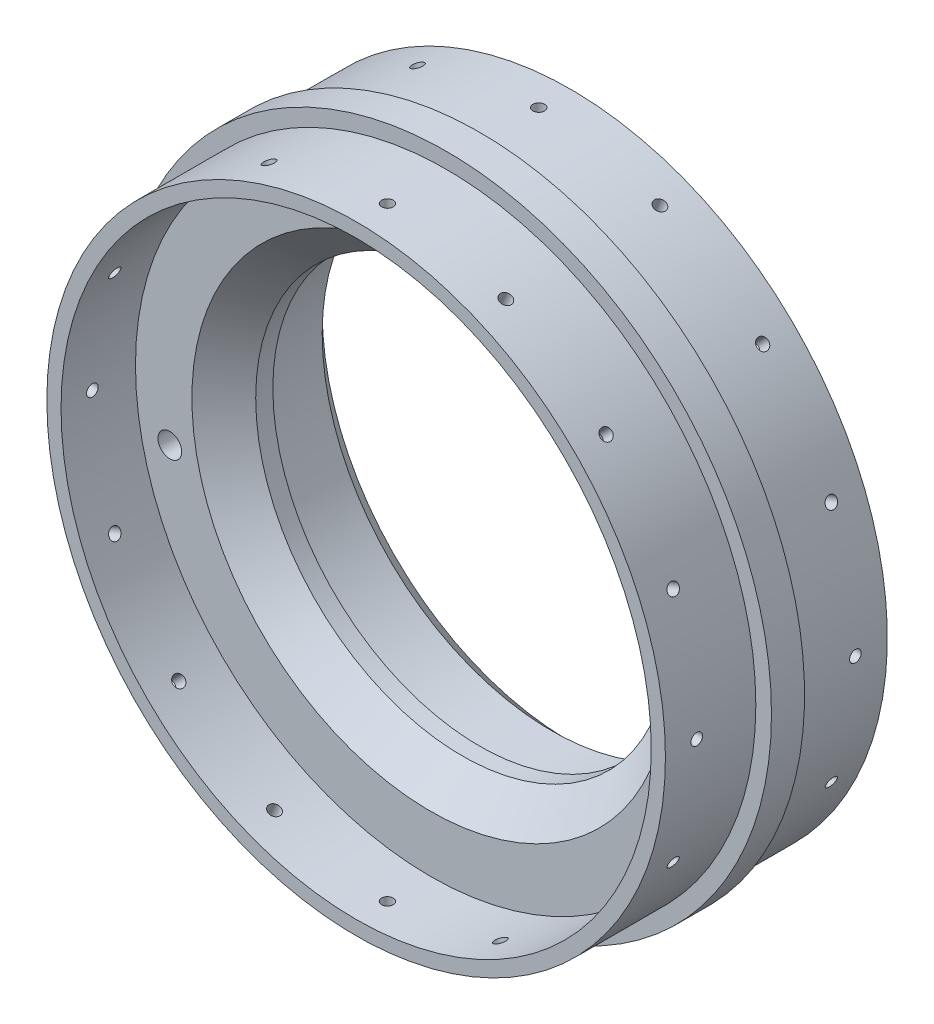
SolidWorks part; units mm, degrees
ref_plane "Front Plane" through (0, 0, 0) normal (0, 0, 1) x (1, 0, 0)
ref_plane "Top Plane" through (0, 0, 0) normal (0, 1, 0) x (1, 0, 0)
ref_plane "Right Plane" through (0, 0, 0) normal (1, 0, 0) x (0, 0, -1)
sketch "Sketch5" plane through (0, 0, 0) normal (0, 0, 1) x (1, 0, 0)
  circle A0 centre (0, 0) radius 69.85
extrude "Extrude1" add sketch "Sketch5" along normal blind 46.101
sketch "Sketch8" plane through (0, 0, 46.101) normal (0, 0, 1) x (1, 0, 0)
  circle A0 centre (0, 0) radius 44.45
extrude "Extrude4" cut sketch "Sketch8" against normal through all
sketch "Sketch6" plane through (0, 0, 46.101) normal (0, 0, 1) x (1, 0, 0)
  circle A0 centre (0, 0) radius 66.4845
extrude "Extrude2" cut sketch "Sketch6" against normal blind 19.431 flip side to cut
sketch "Sketch7" plane through (0, 0, 46.101) normal (0, 0, 1) x (1, 0, 0)
  circle A0 centre (0, 0) radius 63.4365
extrude "Extrude3" cut sketch "Sketch7" against normal blind 16.002
chamfer "Chamfer1" distance 6.858 distance2 6.858 1 edges at (44.45, 0, 30.099)
sketch "Sketch9" plane through (0, 0, 0) normal (0, 0, -1) x (-1, 0, 0)
  circle A0 centre (0, 0) radius 68.0847
extrude "Extrude5" cut sketch "Sketch9" against normal blind 19.558 flip side to cut
sketch "Sketch10" plane through (0, 0, 0) normal (0, 0, -1) x (-1, 0, 0)
  circle A0 centre (0, 0) radius 65.0367
  circle A1 centre (0, 0) radius 53.7845
extrude "Extrude6" cut sketch "Sketch10" against normal blind 9.525
sketch "Sketch11" plane through (0, 0, 0) normal (0, 0, -1) x (-1, 0, 0)
  circle A0 centre (0, 0) radius 49.3395
  dimension "D1" = 98.679
extrude "Extrude7" cut sketch "Sketch11" against normal blind 19.558
chamfer "Chamfer2" distance 4.064 angle 45 1 edges at (-49.3395, 0, 0)
ref_plane "Plane1" through (0, 0, 39.37) normal (0, 0, 1) x (1, 0, 0)
ref_plane "Plane2" through (0, 0, 6.858) normal (0, 0, -1) x (-1, 0, 0)
sketch "Sketch13" plane through (0, 0, 6.858) normal (0, 0, -1) x (-1, 0, 0)
  line L0 (0, 0) -> (0, 68.0847) construction
  circle A0 centre (0, 0) radius 68.0847 construction
ref_plane "Plane3" through (0, 68.0847, 6.858) normal (0, 1, 0) x (-1, 0, 0)
sketch "Sketch15" plane through (0, 0, 39.37) normal (0, 0, 1) x (1, 0, 0)
  line L0 (0, 0) -> (0, 66.4845) construction
  line L1 (0, 0) -> (0, 68.0847) construction
  circle A0 centre (0, 0) radius 66.4845 construction
ref_plane "Plane4" through (0, 66.4845, 39.37) normal (0, 1, 0) x (-1, 0, 0)
hole_wizard "M3x0.5 Tapped Hole2" positions "Sketch20" profile "Sketch19" tap size "M3x0.5" standard "Ansi Metric"
sketch "Sketch20" plane through (0, 68.0847, 6.858) normal (0, 1, 0) x (-1, 0, 0)
  point P1 (0, 0)
sketch "Sketch19" plane through (0, 68.0847, 6.858) normal (1, 0, 0) x (0, 0, 1)
  line L0 (0, 0) -> (0, 9.3871)
  line L1 (0, 9.3871) -> (1.25, 8.636)
  line L2 (1.25, 8.636) -> (1.25, 0)
  line L5 (1.25, 0) -> (0, 0)
  line L10 (0, 9.3871) -> (-1.25, 8.636) construction
  line L11 (0, -6.35) -> (0, 107.95) construction
  dimension "Tap Drill Dia." = 2.5
  dimension "Tap Drill Depth" = 8.636
  dimension "Drill Angle" = 118
cosmetic thread "Hole Thread2" parameters "D1"=3.06, "D2"=3
hole_wizard "M3x0.5 Tapped Hole1" positions "Sketch26" profile "Sketch25" tap size "M3x0.5" standard "Ansi Metric"
sketch "Sketch26" plane through (0, 66.4845, 39.37) normal (0, 1, 0) x (-1, 0, 0)
  point P1 (0, 0)
sketch "Sketch25" plane through (0, 66.4845, 39.37) normal (1, 0, 0) x (0, 0, 1)
  line L0 (0, 0) -> (0, 9.3871)
  line L1 (0, 9.3871) -> (1.25, 8.636)
  line L2 (1.25, 8.636) -> (1.25, 0)
  line L5 (1.25, 0) -> (0, 0)
  line L10 (0, 9.3871) -> (-1.25, 8.636) construction
  line L11 (0, -6.35) -> (0, 107.95) construction
  dimension "Tap Drill Dia." = 2.5
  dimension "Tap Drill Depth" = 8.636
  dimension "Drill Angle" = 118
cosmetic thread "Hole Thread1" parameters "D1"=3.0603, "D2"=3
pattern_circular "CirPattern1" count 16 over 360 about axis through (0, 0, 19.558) along (0, 0, -1) of "M3x0.5 Tapped Hole2", "M3x0.5 Tapped Hole1"
ref_plane "Plane5" through (0, 0, 23.114) normal (0, 0, 1) x (1, 0, 0)
sketch "Sketch27" plane through (0, 0, 23.114) normal (0, 0, 1) x (1, 0, 0)
  line L0 (0, -65.0367) -> (0, -68.0847) construction
  arc A0 (0, -69.85) -> (13.6271, -68.5079) centre (0, 0) ccw construction
  circle A1 centre (0, 0) radius 69.85 construction
ref_plane "Plane6" through (13.6271, -68.5079, 23.114) normal (0.1951, -0.9808, 0) x (0.9808, 0.1951, 0)
hole_wizard "#21 (0.159) Diameter Hole1" positions "Sketch29" profile "Sketch28" hole size "#21" standard "Ansi Inch"
sketch "Sketch29" plane through (13.6271, -68.5079, 23.114) normal (0.1951, -0.9808, 0) x (0.9808, 0.1951, 0)
  point P1 (0, 0)
sketch "Sketch28" plane through (13.6271, -68.5079, 23.114) normal (0, 0, 1) x (0.9808, 0.1951, 0)
  line L0 (0, 0) -> (0, 13.9133)
  line L1 (0, 13.9133) -> (2.0193, 12.7)
  line L2 (2.0193, 12.7) -> (2.0193, 0)
  line L5 (2.0193, 0) -> (0, 0)
  line L10 (0, 13.9133) -> (-2.0193, 12.7) construction
  line L11 (0, -6.35) -> (0, 107.95) construction
  dimension "Hole Dia." = 4.0386
  dimension "Hole Depth" = 12.7
  dimension "Drill Angle" = 118
sketch "Sketch30" plane through (0, 0, 30.099) normal (0, 0, 1) x (1, 0, 0)
  arc A0 (0, -57.15) -> (56.0519, 11.1494) centre (0, 0) ccw construction
hole_wizard "1/4-20 Tapped Hole1" positions "3DSketch1" profile "Sketch31" tap size "1/4-20" standard "Ansi Inch" end condition through all
sketch3d "3DSketch1"
  point P0 (56.0519, 11.1494, 30.099)
sketch "Sketch31" plane through (56.0519, 11.1494, 30.099) normal (1, 0, 0) x (0, -1, 0)
  line L0 (0, 0) -> (0, 30.099)
  line L1 (0, 30.099) -> (2.5527, 30.099)
  line L2 (2.5527, 30.099) -> (2.5527, 0)
  line L5 (2.5527, 0) -> (0, 0)
  line L11 (0, -6.35) -> (0, 107.95) construction
  dimension "Thru Tap Drill Dia." = 5.1054
  dimension "Thru Tap Drill Depth" = 30.099
cosmetic thread "Hole Thread3" parameters "D2"=6.35
pattern_circular "CirPattern2" count 2 over 360 about axis through (0, 0, 0) along (0, 0, 1) of "1/4-20 Tapped Hole1"
